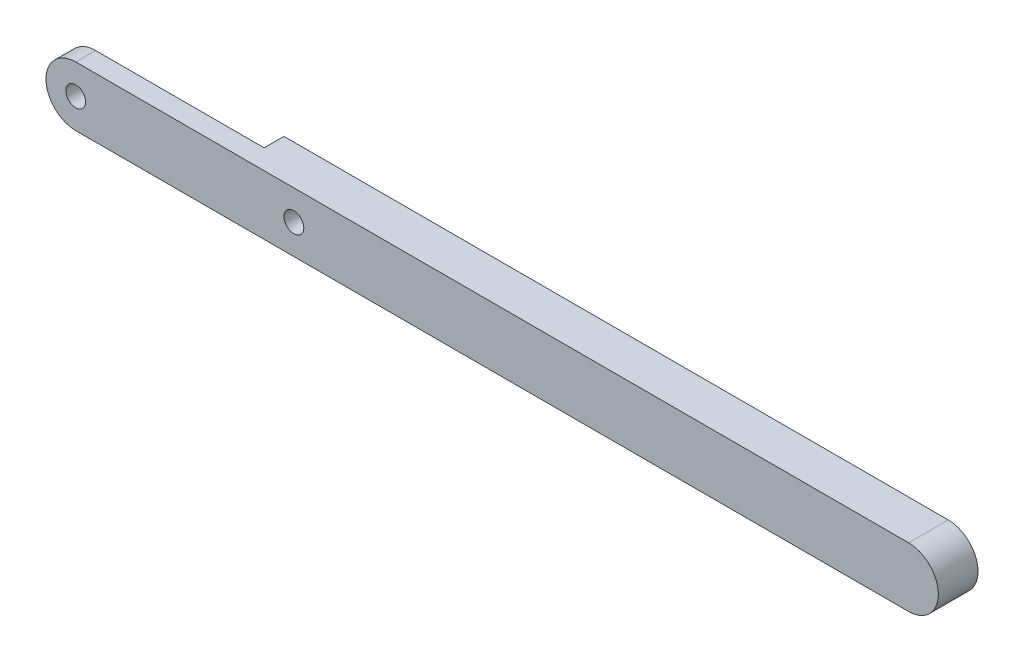
SolidWorks part; units mm, degrees
ref_plane "Front Plane" through (0, 0, 0) normal (0, 0, 1) x (1, 0, 0)
ref_plane "Top Plane" through (0, 0, 0) normal (0, 1, 0) x (1, 0, 0)
ref_plane "Right Plane" through (0, 0, 0) normal (1, 0, 0) x (0, 0, -1)
sketch "Sketch1" plane through (0, 0, 0) normal (0, 0, 1) x (1, 0, 0)
  line L0 (0, 0) -> (420, 0) construction
  line L1 (0, 15) -> (420, 15)
  line L2 (0, -15) -> (420, -15)
  arc A0 (0, 15) -> (0, -15) centre (0, 0) ccw
  arc A1 (420, -15) -> (420, 15) centre (420, 0) ccw
  circle A2 centre (0, 0) radius 5
  circle A3 centre (110, 0) radius 5
  point P3 (210, 0)
  dimension "D2" = 15
  dimension "D3" = 10
  dimension "D4" = 10
  dimension "D1" = 420
  dimension "D5" = 110
extrude "Boss-Extrude1" add sketch "Sketch1" along normal mid plane 20
sketch "Sketch2" plane through (0, 0, 0) normal (0, 0, 1) x (1, 0, 0)
  line L0 (420, 15) -> (0, 15) construction
  line L1 (85, 15) -> (-15, 15)
  line L2 (85, 15) -> (85, -15)
  line L3 (85, -15) -> (-15, -15)
  line L4 (-15, 15) -> (-15, -15)
  dimension "D1" = 100
  dimension "D2" = 30
  dimension "D3" = 15
extrude "Cut-Extrude1" cut sketch "Sketch2" against normal through all
